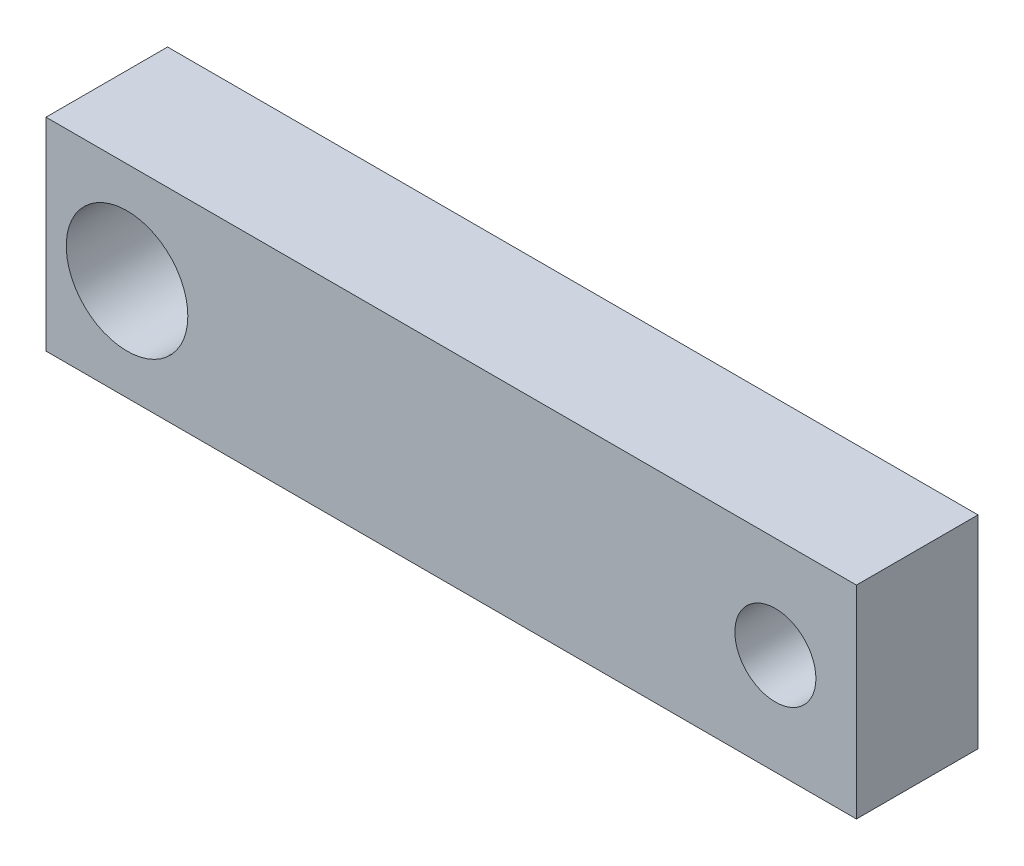
SolidWorks part; units mm, degrees
ref_plane "Front Plane" through (0, 0, 0) normal (0, 0, 1) x (1, 0, 0)
ref_plane "Top Plane" through (0, 0, 0) normal (0, 1, 0) x (1, 0, 0)
ref_plane "Right Plane" through (0, 0, 0) normal (1, 0, 0) x (0, 0, -1)
sketch "Sketch1" plane through (0, 0, 0) normal (0, 0, 1) x (1, 0, 0)
  line L0 (-1000, 0) -> (49000, 0) construction
  line L1 (-10, 2.5) -> (10, 2.5)
  line L2 (-10, 2.5) -> (-10, -2.5)
  line L3 (-10, -2.5) -> (10, -2.5)
  line L4 (10, 2.5) -> (10, -2.5)
  line L5 (-10, 2.5) -> (10, -2.5) construction
  line L6 (-10, -2.5) -> (10, 2.5) construction
  circle A0 centre (8, 0) radius 1
  circle A1 centre (-8, 0) radius 1.5
  point P0 (0, 0)
  dimension "D3" = 2
  dimension "D5" = 3
  dimension "D1" = 5
  dimension "D2" = 20
  dimension "D4" = 2
  dimension "D6" = 2
extrude "Boss-Extrude1" add sketch "Sketch1" along normal blind 3 contours A1 | A0 | L1 L4 L3 L2
